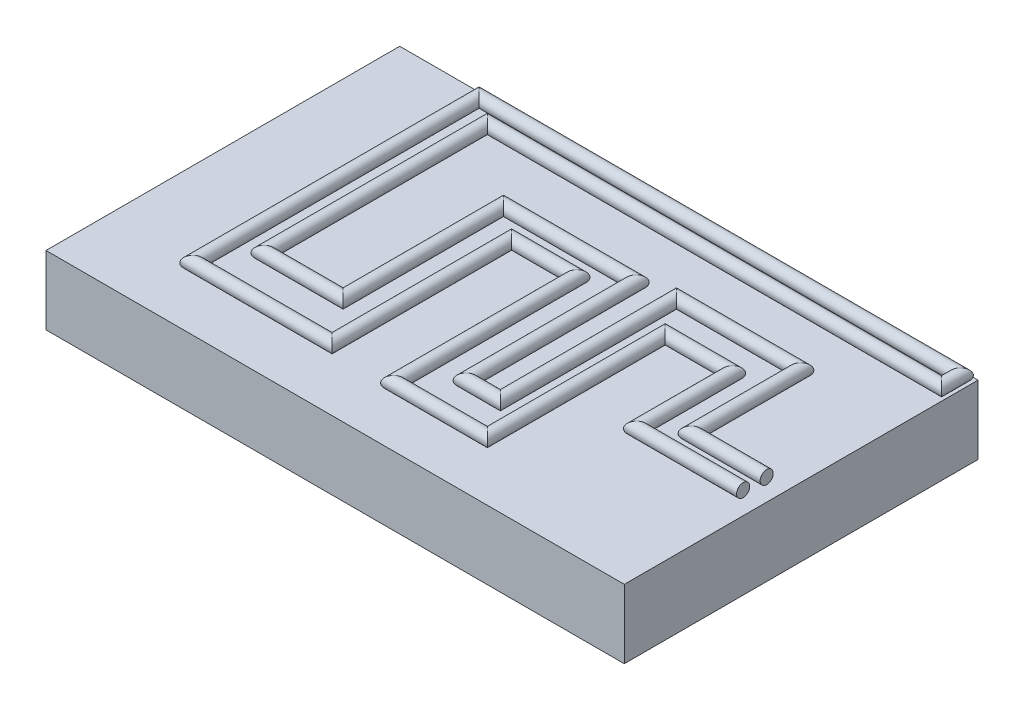
SolidWorks part; units mm, degrees
ref_plane "Front Plane" through (0, 0, 0) normal (0, 0, 1) x (1, 0, 0)
ref_plane "Top Plane" through (0, 0, 0) normal (0, 1, 0) x (1, 0, 0)
ref_plane "Right Plane" through (0, 0, 0) normal (1, 0, 0) x (0, 0, -1)
sketch "Sketch1" plane through (0, 0, 0) normal (0, 1, 0) x (1, 0, 0)
  line L1 (0, 0) -> (61.8, 0)
  line L2 (0, 0) -> (0, 37.8)
  line L3 (0, 37.8) -> (61.8, 37.8)
  line L4 (61.8, 0) -> (61.8, 37.8)
  dimension "D1" = 37.8
  dimension "D2" = 61.8
extrude "Boss-Extrude1" add sketch "Sketch1" along normal blind 7.35
sketch3d "3DSketch1"
  line L0 (11.2927, 9.649, -4.4059) -> (26.1669, 9.649, -4.4059)
  line L2 (26.1669, 9.649, -4.4059) -> (26.1669, 9.649, -23.5867)
  line L3 (26.1669, 9.649, -23.5867) -> (33.1401, 9.649, -23.5867)
  line L4 (14.1728, 9.649, -32.9919) -> (14.1728, 9.649, -9.1335)
  line L5 (0, 3.675, -37.8) -> (0, 3.675, 0) construction
  line L6 (0, 7.35, -37.8) -> (0, 0, -37.8) construction
  line L7 (0, 7.35, 0) -> (0, 0, 0) construction
  line L8 (33.1401, 9.649, -23.5867) -> (33.1401, 9.649, -4.0167)
  line L9 (14.1728, 9.649, -32.9919) -> (62.72, 9.649, -32.9919)
  line L10 (33.1401, 9.649, -4.0167) -> (43.1501, 9.649, -4.0167)
  line L12 (11.2927, 9.649, -34.9919) -> (62.72, 9.649, -34.9919)
  line L13 (62.72, 9.649, -32.9919) -> (62.72, 9.649, -34.9919)
  line L14 (11.2927, 9.649, -4.4059) -> (11.2927, 9.649, -34.9919)
  line L15 (43.1501, 9.649, -4.0167) -> (43.1501, 9.649, -23.0243)
  line L16 (43.1501, 9.649, -23.0243) -> (50.3482, 9.649, -23.0243)
  line L17 (50.3482, 9.649, -23.0243) -> (50.3482, 9.649, -12.7678)
  line L18 (50.3482, 9.649, -12.7678) -> (61.7335, 9.649, -12.7678)
  line L19 (14.1728, 9.649, -9.1335) -> (22.616, 9.649, -9.1335)
  line L20 (22.616, 9.649, -9.1335) -> (22.616, 9.649, -26.2739)
  line L21 (22.616, 9.649, -26.2739) -> (36.7833, 9.649, -26.2739)
  line L22 (36.7833, 9.649, -26.2739) -> (36.7833, 9.649, -8.122)
  line L23 (36.7833, 9.649, -8.122) -> (40.4359, 9.649, -8.122)
  line L24 (40.4359, 9.649, -8.122) -> (40.4359, 9.649, -26.938)
  line L25 (40.4359, 9.649, -26.938) -> (53.7177, 9.649, -26.938)
  line L26 (53.7177, 9.649, -26.938) -> (53.7177, 9.649, -15.236)
  line L27 (53.7177, 9.649, -15.236) -> (61.7814, 9.649, -15.236)
  point P30 (0, 0, 0)
  dimension "D7" = 2
sweep "Sweep10" add path "3DSketch1" circular profile diameter 1.4 parameters "D3"=1.4
